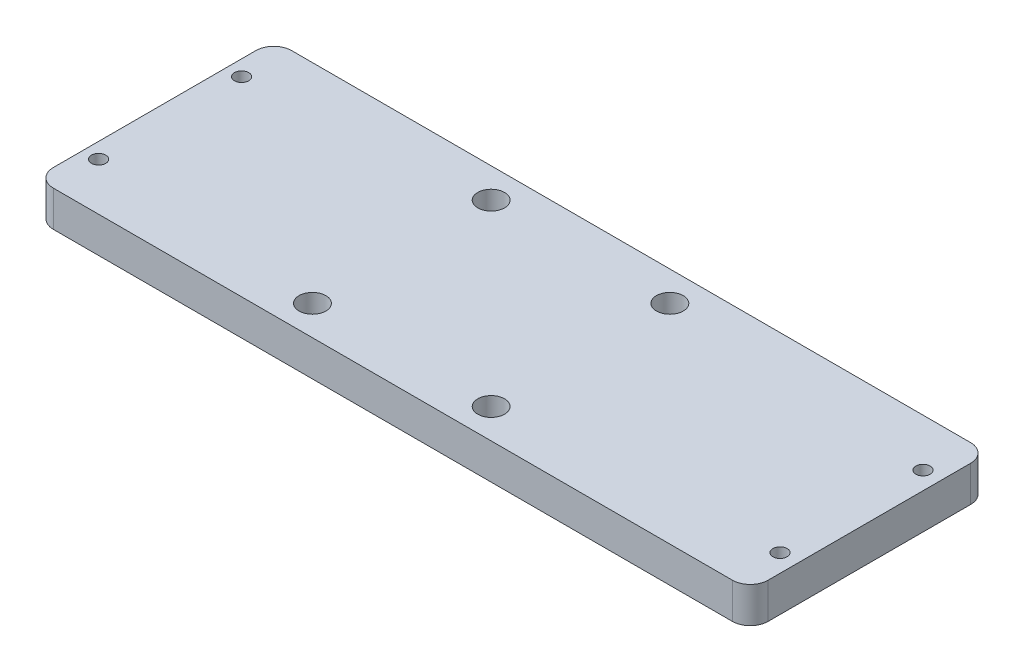
SolidWorks part; units mm, degrees
material "Acrylic (Medium-high impact)"
ref_plane "Front Plane" through (0, 0, 0) normal (0, 0, 1) x (1, 0, 0)
ref_plane "Top Plane" through (0, 0, 0) normal (0, 1, 0) x (1, 0, 0)
ref_plane "Right Plane" through (0, 0, 0) normal (1, 0, 0) x (0, 0, -1)
sketch "Sketch1" plane through (0, 0, 0) normal (0, 1, 0) x (1, 0, 0)
  line L0 (-63.5, 0) -> (63.5, 0) construction
  line L1 (-63.5, 20) -> (63.5, 20)
  line L2 (-63.5, 20) -> (-63.5, -20)
  line L3 (-63.5, -20) -> (63.5, -20)
  line L4 (63.5, 20) -> (63.5, -20)
  line L5 (-63.5, 20) -> (63.5, -20) construction
  line L6 (-63.5, -20) -> (63.5, 20) construction
  line L7 (60.5, 0) -> (60.5, 62.2508) construction
  line L8 (-53.9, 0) -> (-53.9, 64.2354) construction
  line L9 (0, 0) -> (0, 25.04) construction
  line L10 (-15, 15) -> (15, 15) construction
  line L11 (-15, 15) -> (-15, -15) construction
  line L12 (-15, -15) -> (15, -15) construction
  line L13 (15, 15) -> (15, -15) construction
  line L14 (-15, 15) -> (15, -15) construction
  line L15 (-15, -15) -> (15, 15) construction
  circle A0 centre (60.5, 12) radius 1.2
  circle A1 centre (-53.9, 12) radius 1.2
  circle A3 centre (-15, 15) radius 2.25
  circle A4 centre (15, 15) radius 2.25
  circle A5 centre (60.5, -12) radius 1.2
  circle A6 centre (15, -15) radius 2.25
  circle A7 centre (-15, -15) radius 2.25
  circle A8 centre (-53.9, -12) radius 1.2
  point P0 (0, 0)
  point P16 (0, 0)
  point P25 (0, 0)
  dimension "D4" = 2.4
  dimension "D5" = 12
  dimension "D7" = 2.4
  dimension "D8" = 12
  dimension "D10" = 4.5
  dimension "D1" = 40
  dimension "D2" = 127
  dimension "D3" = 3
  dimension "D6" = 114.4
  dimension "D9" = 30
extrude "Boss-Extrude1" add sketch "Sketch1" along normal blind 6
sketch "Sketch2" plane through (-63.5, 0, 0) normal (-1, 0, 0) x (0, 0, 1)
  line L4 (-20, 0) -> (20, 0)
  line L5 (20, 0) -> (20, 6)
  line L6 (20, 6) -> (-20, 6)
  line L7 (-20, 6) -> (-20, 0)
  line L8 (-20, 0) -> (20, 0)
  line L9 (20, 0) -> (20, 6)
  line L10 (20, 6) -> (-20, 6)
  line L11 (-20, 6) -> (-20, 0)
  dimension "D1" = 0
extrude "Cut-Extrude1" cut sketch "Sketch2" against normal blind 7
fillet "Fillet1" radius 3 4 edges at (-56.5, 3, -20) (63.5, 3, -20) (63.5, 3, 20) (-56.5, 3, 20)
